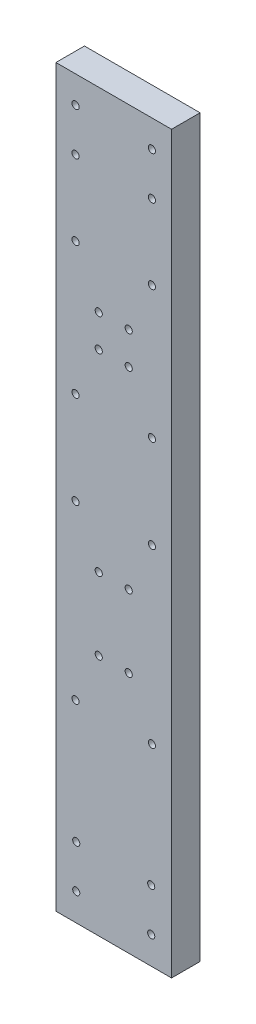
SolidWorks part; units mm, degrees
ref_plane "Front Plane" through (0, 0, 0) normal (0, 0, 1) x (1, 0, 0)
ref_plane "Top Plane" through (0, 0, 0) normal (0, 1, 0) x (1, 0, 0)
ref_plane "Right Plane" through (0, 0, 0) normal (1, 0, 0) x (0, 0, -1)
sketch "Sketch1" plane through (0, 0, 0) normal (0, 0, 1) x (1, 0, 0)
  line L0 (0, 102.97) -> (0, 0)
  line L1 (16.2, 102.97) -> (16.2, 0)
  line L2 (0, 102.97) -> (16.2, 102.97)
  line L3 (0, 0) -> (16.2, 0)
  circle A0 centre (10.2, 71.14) radius 0.5
  circle A1 centre (13.45, 51.14) radius 0.5
  circle A2 centre (13.45, 93.17) radius 0.5
  circle A3 centre (6, 71.14) radius 0.5
  circle A4 centre (2.75, 99.17) radius 0.5
  circle A5 centre (6, 75.67) radius 0.5
  circle A6 centre (2.75, 51.14) radius 0.5
  circle A7 centre (6, 44.14) radius 0.5
  circle A8 centre (13.45, 27) radius 0.5
  circle A9 centre (10.2, 75.67) radius 0.5
  circle A11 centre (6, 34) radius 0.5
  circle A13 centre (2.75, 27) radius 0.5
  circle A16 centre (2.75, 93.17) radius 0.5
  circle A17 centre (13.45, 82.67) radius 0.5
  circle A19 centre (13.45, 64.14) radius 0.5
  circle A20 centre (13.45, 99.17) radius 0.5
  circle A21 centre (10.2, 44.14) radius 0.5
  circle A22 centre (2.75, 82.67) radius 0.5
  circle A23 centre (2.85, 9.8464) radius 0.5
  circle A24 centre (13.35, 9.8464) radius 0.5
  circle A25 centre (13.35, 3.8464) radius 0.5
  circle A26 centre (2.85, 3.8464) radius 0.5
  circle A27 centre (2.75, 64.14) radius 0.5
  circle A30 centre (10.2, 34) radius 0.5
extrude "Boss-Extrude1" add sketch "Sketch1" along normal blind 4
